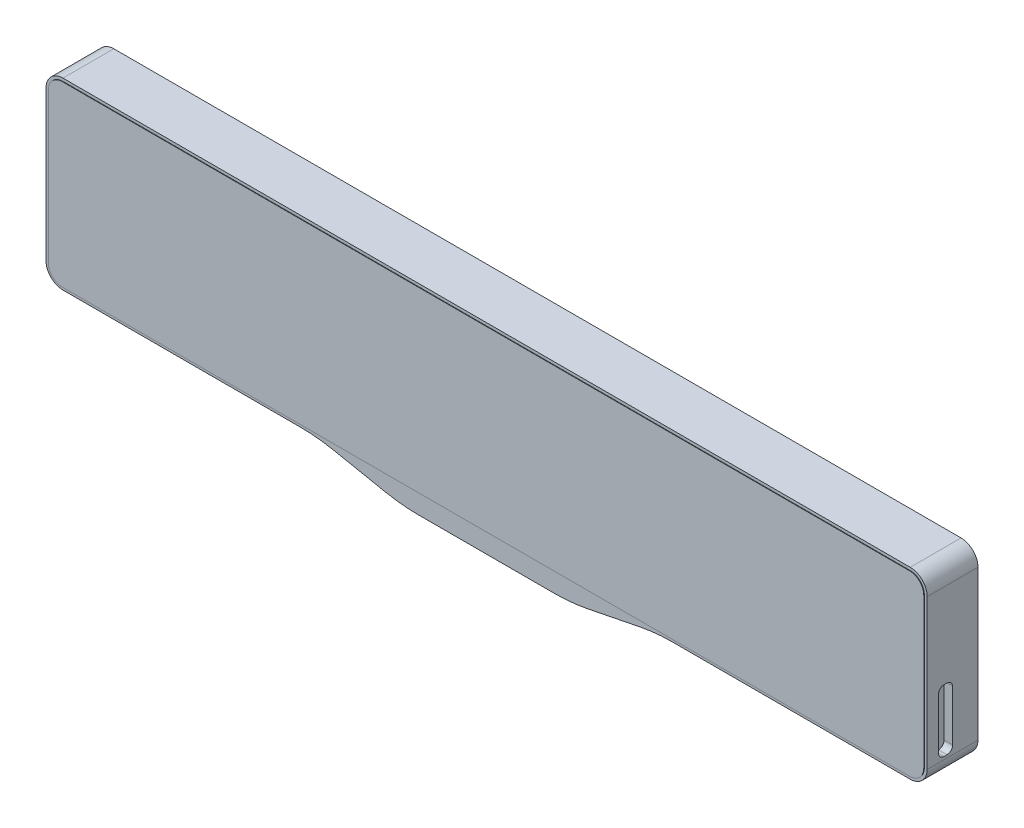
SolidWorks part; units mm, degrees
ref_plane "Front Plane" through (0, 0, 0) normal (0, 0, 1) x (1, 0, 0)
ref_plane "Top Plane" through (0, 0, 0) normal (0, 1, 0) x (1, 0, 0)
ref_plane "Right Plane" through (0, 0, 0) normal (1, 0, 0) x (0, 0, -1)
sketch "Sketch1" plane through (0, 0, 0) normal (0, 0, 1) x (1, 0, 0)
  line L0 (0, 0) -> (0, -16.25) construction
  line L1 (78, -16.25) -> (-78, -16.25) construction
  line L2 (78, -16.25) -> (78, 16.25)
  line L3 (78, 16.25) -> (-78, 16.25)
  line L4 (-78, -16.25) -> (-78, 16.25)
  line L5 (78, -16.25) -> (-78, 16.25) construction
  line L6 (78, 16.25) -> (-78, -16.25) construction
  line L7 (-15, -19.25) -> (15, -19.25)
  line L8 (15, -19.25) -> (30, -16.25)
  line L9 (30, -16.25) -> (78, -16.25)
  line L10 (-15, -19.25) -> (-30, -16.25)
  line L11 (-30, -16.25) -> (-78, -16.25)
  point P0 (0, 0)
  point P12 (0, -19.25)
  dimension "D1" = 32.5
  dimension "D2" = 156
  dimension "D3" = 35.5
  dimension "D4" = 30
  dimension "D5" = 60
extrude "Boss-Extrude1" add sketch "Sketch1" along normal blind 9
fillet "Fillet1" radius 30 4 edges at (-30, -16.25, 4.5) (30, -16.25, 4.5) (15, -19.25, 4.5) (-15, -19.25, 4.5)
fillet "Fillet2" radius 3 4 edges at (78, 16.25, 4.5) (78, -16.25, 4.5) (-78, 16.25, 4.5) (-78, -16.25, 4.5)
sketch "Sketch2" plane through (0, 0, 9) normal (0, 0, 1) x (1, 0, 0)
  line L8 (-32.9706, -15.75) -> (32.9706, -15.75)
  line L16 (77.5, -13.25) -> (77.5, 13.25)
  line L17 (75, 15.75) -> (-75, 15.75)
  line L18 (-77.5, 13.25) -> (-77.5, -13.25)
  line L19 (-75, -15.75) -> (-32.9706, -15.75)
  line L20 (-26.989, -16.3423) -> (-17.8148, -18.1771)
  line L21 (-12.0294, -18.75) -> (12.0294, -18.75)
  line L22 (17.8148, -18.1771) -> (26.989, -16.3423)
  line L23 (32.9706, -15.75) -> (75, -15.75)
  line L24 (77.5, -13.25) -> (77.5, 13.25)
  line L25 (75, 15.75) -> (-75, 15.75)
  line L26 (-77.5, 13.25) -> (-77.5, -13.25)
  line L27 (-75, -15.75) -> (-32.9706, -15.75)
  line L31 (32.9706, -15.75) -> (75, -15.75)
  arc A16 (77.5, 13.25) -> (75, 15.75) centre (75, 13.25) ccw
  arc A17 (-75, 15.75) -> (-77.5, 13.25) centre (-75, 13.25) ccw
  arc A18 (-77.5, -13.25) -> (-75, -15.75) centre (-75, -13.25) ccw
  arc A19 (-26.989, -16.3423) -> (-32.9706, -15.75) centre (-32.9706, -46.25) ccw
  arc A20 (-17.8148, -18.1771) -> (-12.0294, -18.75) centre (-12.0294, 10.75) ccw
  arc A21 (12.0294, -18.75) -> (17.8148, -18.1771) centre (12.0294, 10.75) ccw
  arc A22 (32.9706, -15.75) -> (26.989, -16.3423) centre (32.9706, -46.25) ccw
  arc A23 (75, -15.75) -> (77.5, -13.25) centre (75, -13.25) ccw
  arc A24 (77.5, 13.25) -> (75, 15.75) centre (75, 13.25) ccw
  arc A25 (-75, 15.75) -> (-77.5, 13.25) centre (-75, 13.25) ccw
  arc A26 (-77.5, -13.25) -> (-75, -15.75) centre (-75, -13.25) ccw
  arc A31 (75, -15.75) -> (77.5, -13.25) centre (75, -13.25) ccw
  dimension "D1" = 0.5
extrude "Boss-Extrude2" add sketch "Sketch2" along normal blind 0.1
sketch "Sketch3" plane through (0, -19.25, 0) normal (0, -1, 0) x (1, 0, 0)
  line L0 (0, 0) -> (0, 9) construction
  line L1 (-12.0294, 9) -> (12.0294, 9) construction
  line L2 (-9, 4.5) -> (0, 4.5) construction
  circle A0 centre (-9, 4.5) radius 1.2
  circle A1 centre (9, 4.5) radius 1.2
  dimension "D1" = 2.4
  dimension "D2" = 18
extrude "Cut-Extrude1" cut sketch "Sketch3" against normal blind 5
sketch "Sketch4" plane through (-78, 0, 0) normal (-1, 0, 0) x (0, 0, 1)
  line L0 (0, 13.25) -> (0, -13.25) construction
  line L1 (4, 6.25) -> (7.5, 6.25)
  line L2 (4, 6.25) -> (4, -8.25)
  line L3 (4, -8.25) -> (7.5, -8.25)
  line L4 (7.5, 6.25) -> (7.5, -8.25)
  line L5 (9, 13.25) -> (9, -13.25) construction
  line L6 (0, 16.25) -> (9, 16.25) construction
  line L7 (9, -16.25) -> (0, -16.25) construction
  dimension "D1" = 4
  dimension "D2" = 1.5
  dimension "D3" = 10
  dimension "D4" = 8
extrude "Cut-Extrude2" cut sketch "Sketch4" against normal blind 1.5
sketch "Sketch5" plane through (78, 0, 0) normal (1, 0, 0) x (0, 0, -1)
  line L0 (0, -16.25) -> (-9, -16.25) construction
  line L1 (-7, -1.75) -> (-4.5, -1.75)
  line L2 (-7, -1.75) -> (-7, -12.75)
  line L3 (-7, -12.75) -> (-4.5, -12.75)
  line L4 (-4.5, -1.75) -> (-4.5, -12.75)
  line L5 (-9, -13.25) -> (-9, 13.25) construction
  line L6 (0, -13.25) -> (0, 13.25) construction
  line L7 (-9, 16.25) -> (0, 16.25) construction
  dimension "D1" = 3.5
  dimension "D2" = 2
  dimension "D3" = 4.5
  dimension "D4" = 18
extrude "Cut-Extrude4" cut sketch "Sketch5" against normal blind 1.5
fillet "Fillet3" radius 1 8 edges at (-77.25, -8.25, 7.5) (-77.25, -8.25, 4) (-77.25, 6.25, 7.5) (-77.25, 6.25, 4) (77.25, -12.75, 4.5) (77.25, -1.75, 7) (77.25, -12.75, 7) (77.25, -1.75, 4.5)
